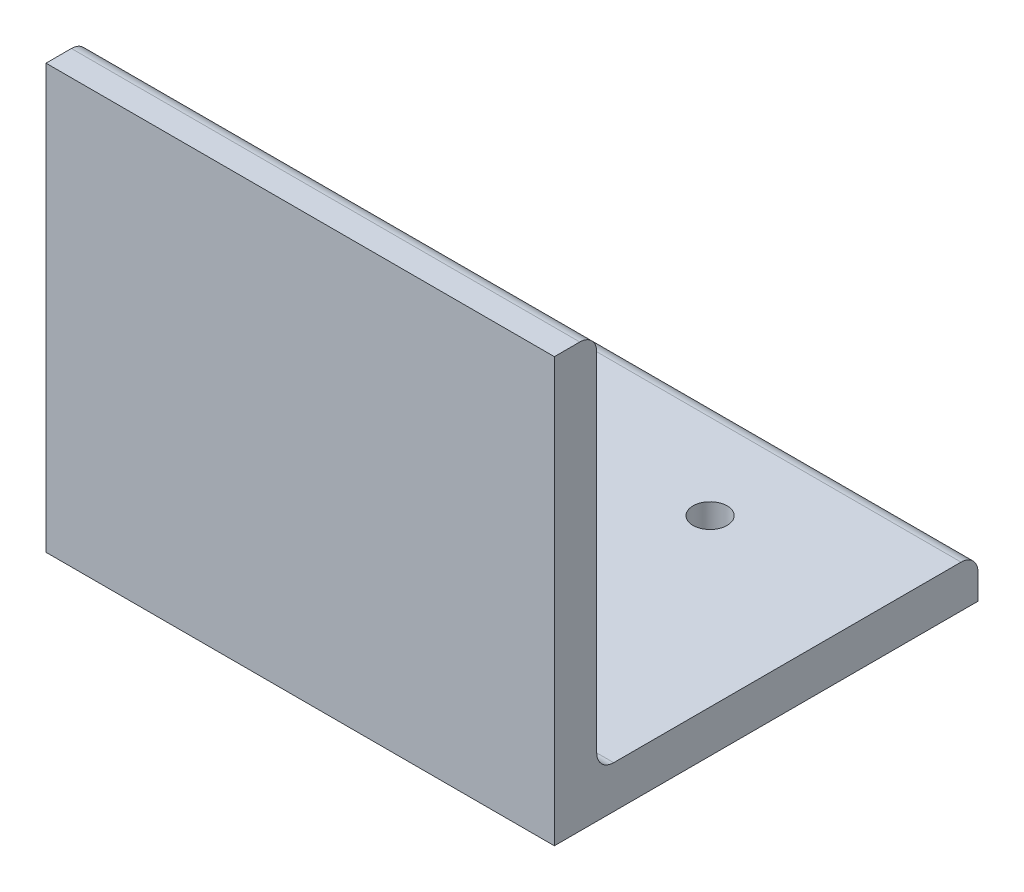
SolidWorks part; units mm, degrees
ref_plane "Front Plane" through (0, 0, 0) normal (0, 0, 1) x (1, 0, 0)
ref_plane "Top Plane" through (0, 0, 0) normal (0, 1, 0) x (1, 0, 0)
ref_plane "Right Plane" through (0, 0, 0) normal (1, 0, 0) x (0, 0, -1)
sketch "Sketch1" plane through (0, 0, 0) normal (1, 0, 0) x (0, 0, -1)
  line L2 (0, 0) -> (0, 63.5)
  line L3 (0, 63.5) -> (3.81, 63.5)
  line L4 (6.35, 8.89) -> (6.35, 60.96)
  line L5 (0, 0) -> (63.5, 0)
  line L7 (8.89, 6.35) -> (60.96, 6.35)
  line L8 (63.5, 0) -> (63.5, 3.81)
  arc A0 (3.81, 63.5) -> (6.35, 60.96) centre (3.81, 60.96) cw
  arc A1 (60.96, 6.35) -> (63.5, 3.81) centre (60.96, 3.81) cw
  arc A2 (8.89, 6.35) -> (6.35, 8.89) centre (8.89, 8.89) cw
  point P12 (6.35, 63.5)
  dimension "D5" = 2.54
  dimension "D1" = 6.35
  dimension "D2" = 63.5
extrude "Boss-Extrude2" add sketch "Sketch1" along normal blind 76.2
hole_wizard "CSK for #10 Flat Head Machine Screw (100)1" positions "Sketch2" profile "Sketch3" countersink size "#10" standard "ANSI Inch" end condition up to next
sketch "Sketch2" plane through (0, 0, 0) normal (0, 1, 0) x (1, 0, 0)
  line L2 (24.8417, 21.6667) -> (51.3583, 21.6667)
  line L3 (24.8417, 21.6667) -> (24.8417, 48.1833)
  line L4 (24.8417, 48.1833) -> (51.3583, 48.1833)
  line L5 (51.3583, 21.6667) -> (51.3583, 48.1833)
  line L6 (24.8417, 21.6667) -> (51.3583, 48.1833) construction
  line L7 (24.8417, 48.1833) -> (51.3583, 21.6667) construction
  line L8 (76.2, 0) -> (0, 0) construction
  line L9 (76.2, 0) -> (0, 0) construction
  line L10 (38.1, 0) -> (38.1, 34.925) construction
  point P0 (24.8417, 48.1833)
  point P2 (51.3583, 48.1833)
  point P4 (51.3583, 21.6667)
  point P6 (24.8417, 21.6667)
  dimension "D1" = 37.5
  dimension "D2" = 34.925
sketch "Sketch3" plane through (24.8417, 0, -48.1833) normal (1, 0, 0) x (0, 0, -1)
  line L0 (0, 0) -> (0, 6.35)
  line L1 (0, 6.35) -> (2.5527, 6.35)
  line L2 (2.5527, 6.35) -> (2.5527, 1.9608)
  line L3 (2.5527, 1.9608) -> (4.8895, 0)
  line L5 (4.8895, 0) -> (0, 0)
  line L6 (-2.5527, 1.9608) -> (-4.8895, 0) construction
  line L11 (0, -6.35) -> (0, 107.95) construction
  dimension "Thru Hole Dia." = 5.1054
  dimension "Thru Hole Depth" = 6.35
  dimension "Near C'Sink Dia." = 9.779
  dimension "Near C'Sink Angle" = 100
